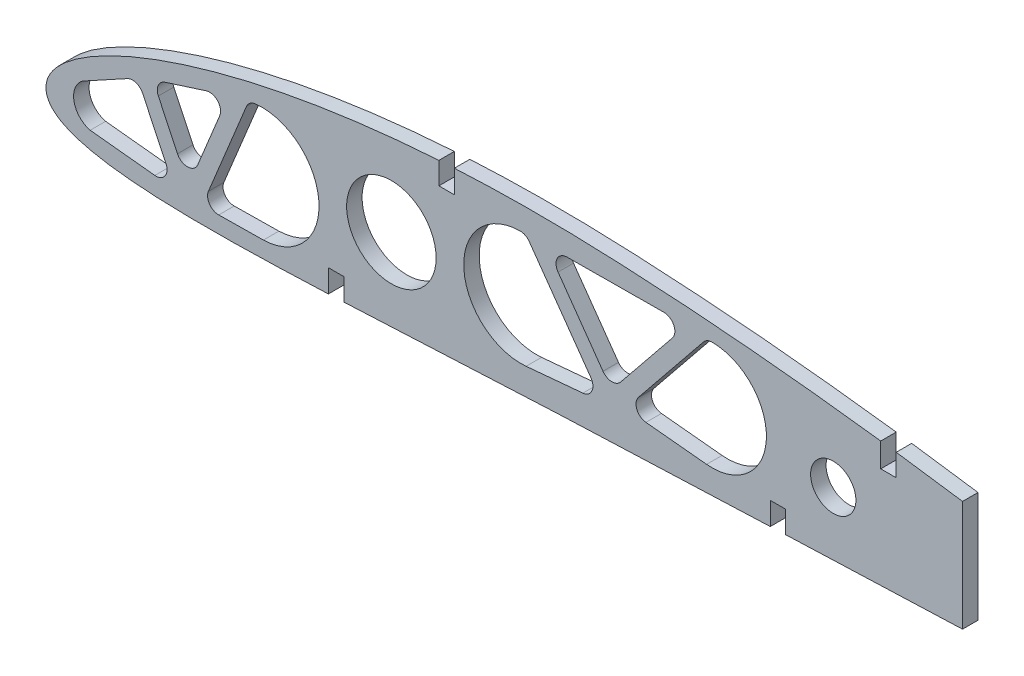
SolidWorks part; units mm, degrees
material "фанера"
ref_plane "Front" through (0, 0, 0) normal (0, 0, 1) x (1, 0, 0)
ref_plane "Top" through (0, 0, 0) normal (0, 1, 0) x (1, 0, 0)
ref_plane "Right" through (0, 0, 0) normal (1, 0, 0) x (0, 0, -1)
curve "Кривая1"
  spline degree 3 poles (0.048, 0.6214, 0) (0.0227, 0.3735, 0) (-0.0278, -0.1225, 0) (0.078, -0.8844, 0) (0.3497, -1.6388, 0) (0.8143, -2.3651, 0) (1.4635, -3.0393, 0) (2.291, -3.661, 0) (3.3059, -4.2358, 0) (4.5353, -4.7737, 0) (6.0297, -5.2822, 0) (7.869, -5.7653, 0) (10.1688, -6.2217, 0) (13.0754, -6.6396, 0) (16.7281, -6.993, 0) (21.19, -7.2473, 0) (26.4, -7.3766, 0) (32.1974, -7.3763, 0) (38.3978, -7.2614, 0) (44.8576, -7.0566, 0) (51.4865, -6.7865, 0) (58.231, -6.4723, 0) (65.0521, -6.1329, 0) (71.9108, -5.784, 0) (78.7714, -5.4397, 0) (85.6105, -5.111, 0) (92.4321, -4.805, 0) (99.255, -4.532, 0) (106.0974, -4.2783, 0) (112.9692, -4.0031, 0) (119.8644, -3.7232, 0) (126.7739, -3.4401, 0) (133.6816, -3.1587, 0) (140.5819, -2.8824, 0) (147.472, -2.6139, 0) (154.3526, -2.3556, 0) (161.225, -2.1094, 0) (168.0909, -1.8766, 0) (174.9516, -1.6586, 0) (181.8086, -1.4564, 0) (188.6632, -1.2704, 0) (195.5166, -1.1011, 0) (202.3695, -0.9486, 0) (209.2212, -0.8129, 0) (216.0668, -0.6936, 0) (222.8864, -0.5903, 0) (229.6176, -0.5029, 0) (236.0874, -0.4315, 0) (241.9808, -0.3765, 0) (246.559, -0.3395, 0) (249.1205, -0.3213, 0) (250, -0.315, 0) knots 0 0 0 0 0.002941 0.005884 0.009016 0.012365 0.016008 0.020037 0.024574 0.029784 0.035897 0.04324 0.052276 0.063635 0.077983 0.095698 0.11652 0.139661 0.164312 0.189919 0.216157 0.242838 0.269834 0.296993 0.324123 0.351139 0.378036 0.404946 0.431961 0.459078 0.486347 0.513641 0.540929 0.568176 0.59538 0.622543 0.649673 0.676775 0.703855 0.730919 0.757971 0.785018 0.812062 0.839103 0.866132 0.893099 0.919831 0.94581 0.969681 0.98959 1 1 1 1
curve "Кривая2"
  spline degree 3 poles (250, 0.315, 0) (249.1557, 0.545, 0) (246.7202, 1.2085, 0) (242.3913, 2.3583, 0) (236.8498, 3.7876, 0) (230.7799, 5.298, 0) (224.4559, 6.8129, 0) (218.0305, 8.2916, 0) (211.5624, 9.7197, 0) (205.0724, 11.0924, 0) (198.568, 12.4079, 0) (192.0524, 13.6653, 0) (185.5276, 14.8641, 0) (178.9953, 16.0034, 0) (172.4571, 17.0824, 0) (165.9143, 18.0998, 0) (159.3687, 19.0545, 0) (152.8218, 19.9449, 0) (146.2754, 20.7693, 0) (139.7314, 21.5257, 0) (133.1918, 22.212, 0) (126.6587, 22.8257, 0) (120.1368, 23.364, 0) (113.6286, 23.8247, 0) (107.1527, 24.2002, 0) (100.7411, 24.4984, 0) (94.4118, 24.6866, 0) (88.1559, 24.7401, 0) (81.949, 24.6588, 0) (75.7805, 24.441, 0) (69.6537, 24.0819, 0) (63.5754, 23.578, 0) (57.5552, 22.9249, 0) (51.6058, 22.1191, 0) (45.7444, 21.1566, 0) (39.9959, 20.0354, 0) (34.3979, 18.7563, 0) (29.0104, 17.3276, 0) (23.9258, 15.7719, 0) (19.2707, 14.1343, 0) (15.1791, 12.4833, 0) (11.7405, 10.8956, 0) (8.9594, 9.4296, 0) (6.7609, 8.1086, 0) (5.0337, 6.9246, 0) (3.6717, 5.8542, 0) (2.5921, 4.8713, 0) (1.7382, 3.9526, 0) (1.0699, 3.0809, 0) (0.5716, 2.2416, 0) (0.2158, 1.4308, 0) (0.1023, 0.8832, 0) (0.048, 0.6214, 0) knots 0 0 0 0 0.010162 0.029313 0.052012 0.076619 0.101948 0.127526 0.153184 0.178868 0.204558 0.230246 0.255926 0.281594 0.307246 0.332878 0.358485 0.384061 0.409603 0.435104 0.460559 0.485959 0.511303 0.536552 0.561723 0.586629 0.611085 0.635251 0.659272 0.683164 0.706922 0.730536 0.753983 0.777235 0.800246 0.822951 0.845237 0.866916 0.887662 0.906968 0.924203 0.938879 0.950932 0.960693 0.968647 0.975233 0.980795 0.985584 0.989782 0.993521 0.996902 1 1 1 1
sketch "Эскиз2" plane through (0, 0, 0) normal (0, 0, 1) x (1, 0, 0)
  line L0 (-1.2592, 0) -> (250.7702, 0) construction
  line L1 (250.1305, 0) -> (250.1305, 80.0888) construction
  line L2 (0, 0) -> (0, 69.7453) construction
  line L3 (62.5326, 123.1249) -> (62.5326, -48.5934) construction
  line L4 (142.5326, 131.1199) -> (142.5326, -55.0117) construction
  line L5 (62.5326, 8.5962) -> (142.5326, 8.5962) construction
  line L6 (62.5326, 8.5962) -> (150.6431, 8.5962) construction
  line L7 (175.0913, 92.567) -> (175.0913, -39.4544) construction
  line L8 (165.9405, 18.0854) -> (165.9405, -1.9504)
  line L9 (87.4969, 19.5968) -> (98.657, 3.8464)
  line L12 (107.2666, 5.069) -> (119.0427, 19.6405)
  line L13 (92.7103, 17.4282) -> (100.8475, 5.9439)
  line L14 (104.0349, 5.843) -> (113.4136, 17.4479)
  line L15 (108.6238, 1.8217) -> (119.6039, 0.7278)
  line L16 (94.3284, 20.5844) -> (111.8443, 20.705)
  line L17 (86.9285, -0.2347) -> (97.2059, 0.6983)
  line L18 (17.4887, 7.868) -> (21.7254, -1.0733)
  line L19 (29.4016, -1.5679) -> (36.2887, 15.1777)
  line L20 (20.3422, 8.8519) -> (23.813, 1.5271)
  line L21 (27.4701, 1.6228) -> (31.461, 11.3265)
  line L22 (7.9994, -2.6904) -> (19.7094, -3.9188)
  line L23 (31.2779, -4.3285) -> (39.3668, -4.221)
  line L24 (6.5801, 4.311) -> (14.7212, 8.7661)
  line L25 (21.5421, 11.6138) -> (29.0038, 13.9928)
  line L26 (72.5326, 27.406) -> (72.5326, 20.4403) construction
  line L27 (52.5326, -12.1202) -> (52.5326, -2.6904) construction
  line L28 (152.5326, 24.4982) -> (152.5326, 15.921) construction
  line L29 (132.5326, -7.5811) -> (132.5326, 3.1811) construction
  line L30 (151.1326, 20.1529) -> (151.1326, 15.7875)
  line L31 (151.1326, 15.7875) -> (153.9326, 15.7875)
  line L32 (153.9326, 15.7875) -> (153.9326, 19.7875)
  line L33 (131.1326, -3.2627) -> (131.1326, 0.8506)
  line L34 (131.1326, 0.8506) -> (133.9326, 0.8506)
  line L35 (133.9326, 0.8506) -> (133.9326, -3.1494)
  line L36 (71.1326, 24.1575) -> (71.1326, 20.1575)
  line L37 (71.1326, 20.1575) -> (73.9326, 20.1575)
  line L38 (73.9326, 20.1575) -> (73.9326, 24.3239)
  line L39 (51.1326, -6.7954) -> (51.1326, -2.6707)
  line L40 (51.1326, -2.6707) -> (53.9326, -2.6707)
  line L41 (53.9326, -2.6707) -> (53.9326, -6.6707)
  arc A0 (250, 0.315) -> (250, -0.315) centre (249.685, 0) cw
  circle A3 centre (62.5326, 8.5962) radius 8.1
  circle A5 centre (62.5326, 8.5962) radius 80 construction
  circle A6 centre (142.5326, 8.5962) radius 4.1
  arc A7 (175.0913, 16.6448) -> (175.0913, -1.657) centre (175.0913, 7.4939) ccw
  arc A10 (107.2666, 5.069) -> (108.6238, 1.8217) centre (108.8221, 3.8118) ccw
  arc A11 (85.8347, 20.4403) -> (86.9285, -0.2347) centre (85.9919, 10.0822) ccw
  arc A12 (120.6027, 20.3833) -> (119.6039, 0.7278) centre (120.5806, 10.5313) cw
  arc A13 (120.6027, 20.3833) -> (119.0427, 19.6405) centre (120.5982, 18.3834) ccw
  arc A14 (85.8347, 20.4403) -> (87.4969, 19.5968) centre (85.8651, 18.4406) cw
  arc A15 (100.8475, 5.9439) -> (104.0349, 5.843) centre (102.4794, 7.1001) ccw
  arc A16 (37.9117, 16.4041) -> (36.2887, 15.1777) centre (38.1384, 14.417) ccw
  arc A17 (98.657, 3.8464) -> (97.2059, 0.6983) centre (97.0251, 2.6901) cw
  arc A18 (92.7103, 17.4282) -> (94.3284, 20.5844) centre (94.3421, 18.5845) cw
  arc A19 (113.4136, 17.4479) -> (111.8443, 20.705) centre (111.8581, 18.7051) ccw
  arc A20 (6.5801, 4.311) -> (7.9994, -2.6904) centre (8.9558, 1.1481) ccw
  arc A21 (37.9117, 16.4041) -> (39.3668, -4.221) centre (39.0848, 6.123) cw
  arc A22 (23.813, 1.5271) -> (27.4701, 1.6228) centre (25.6204, 2.3835) ccw
  arc A23 (31.461, 11.3265) -> (29.0038, 13.9928) centre (29.6113, 12.0873) ccw
  arc A24 (20.3422, 8.8519) -> (21.5421, 11.6138) centre (22.1496, 9.7083) cw
  arc A25 (17.4887, 7.868) -> (14.7212, 8.7661) centre (15.6813, 7.0116) ccw
  arc A26 (19.7094, -3.9188) -> (21.7254, -1.0733) centre (19.9181, -1.9297) ccw
  arc A27 (29.4016, -1.5679) -> (31.2779, -4.3285) centre (31.2513, -2.3286) ccw
  circle A28 centre (175.0913, 7.4939) radius 1
  spline S0 degree 3 poles (250, 0.315) (249.1557, 0.545) (246.7202, 1.2085) (242.3913, 2.3583) (236.8498, 3.7876) (230.7799, 5.298) (224.4559, 6.8129) (218.0305, 8.2916) (211.5624, 9.7197) (205.0724, 11.0924) (198.568, 12.4079) (192.0524, 13.6653) (185.5276, 14.8641) (178.9953, 16.0034) (172.4571, 17.0824) (165.9143, 18.0998) (159.3687, 19.0545) (152.8218, 19.9449) (146.2754, 20.7693) (139.7314, 21.5257) (133.1918, 22.212) (126.6587, 22.8257) (120.1368, 23.364) (113.6286, 23.8247) (107.1527, 24.2002) (100.7411, 24.4984) (94.4118, 24.6866) (88.1559, 24.7401) (81.949, 24.6588) (75.7805, 24.441) (69.6537, 24.0819) (63.5754, 23.578) (57.5552, 22.9249) (51.6058, 22.1191) (45.7444, 21.1566) (39.9959, 20.0354) (34.3979, 18.7563) (29.0104, 17.3276) (23.9258, 15.7719) (19.2707, 14.1343) (15.1791, 12.4833) (11.7405, 10.8956) (8.9594, 9.4296) (6.7609, 8.1086) (5.0337, 6.9246) (3.6717, 5.8542) (2.5921, 4.8713) (1.7382, 3.9526) (1.0699, 3.0809) (0.5716, 2.2416) (0.2158, 1.4308) (0.1023, 0.8832) (0.048, 0.6214) knots 0 0 0 0 0.010162 0.029313 0.052012 0.076619 0.101948 0.127526 0.153184 0.178868 0.204558 0.230246 0.255926 0.281594 0.307246 0.332878 0.358485 0.384061 0.409603 0.435104 0.460559 0.485959 0.511303 0.536552 0.561723 0.586629 0.611085 0.635251 0.659272 0.683164 0.706922 0.730536 0.753983 0.777235 0.800246 0.822951 0.845237 0.866916 0.887662 0.906968 0.924203 0.938879 0.950932 0.960693 0.968647 0.975233 0.980795 0.985584 0.989782 0.993521 0.996902 1 1 1 1 construction
  spline S1 degree 3 poles (0.048, 0.6214) (0.0227, 0.3735) (-0.0278, -0.1225) (0.078, -0.8844) (0.3497, -1.6388) (0.8143, -2.3651) (1.4635, -3.0393) (2.291, -3.661) (3.3059, -4.2358) (4.5353, -4.7737) (6.0297, -5.2822) (7.869, -5.7653) (10.1688, -6.2217) (13.0754, -6.6396) (16.7281, -6.993) (21.19, -7.2473) (26.4, -7.3766) (32.1974, -7.3763) (38.3978, -7.2614) (44.8576, -7.0566) (51.4865, -6.7865) (58.231, -6.4723) (65.0521, -6.1329) (71.9108, -5.784) (78.7714, -5.4397) (85.6105, -5.111) (92.4321, -4.805) (99.255, -4.532) (106.0974, -4.2783) (112.9692, -4.0031) (119.8644, -3.7232) (126.7739, -3.4401) (133.6816, -3.1587) (140.5819, -2.8824) (147.472, -2.6139) (154.3526, -2.3556) (161.225, -2.1094) (168.0909, -1.8766) (174.9516, -1.6586) (181.8086, -1.4564) (188.6632, -1.2704) (195.5166, -1.1011) (202.3695, -0.9486) (211.4992, -0.7677) (220.6031, -0.6199) (229.6176, -0.5029) (236.0874, -0.4315) (241.9808, -0.3765) (246.559, -0.3395) (249.1205, -0.3213) (250, -0.315) knots 0 0 0 0 0.002941 0.005884 0.009016 0.012365 0.016008 0.020037 0.024574 0.029784 0.035897 0.04324 0.052276 0.063635 0.077983 0.095698 0.11652 0.139661 0.164312 0.189919 0.216157 0.242838 0.269834 0.296993 0.324123 0.351139 0.378036 0.404946 0.431961 0.459078 0.486347 0.513641 0.540929 0.568176 0.59538 0.622543 0.649673 0.676775 0.703855 0.730919 0.757971 0.785018 0.812062 0.839103 0.893099 0.919831 0.94581 0.969681 0.98959 1 1 1 1 construction
  spline S2 degree 3 poles (250, 0.315) (249.1557, 0.545) (246.7202, 1.2085) (242.3913, 2.3583) (236.8498, 3.7876) (230.7799, 5.298) (224.4559, 6.8129) (218.0305, 8.2916) (211.5624, 9.7197) (205.0724, 11.0924) (198.568, 12.4079) (192.0524, 13.6653) (185.5276, 14.8641) (178.9953, 16.0034) (172.4571, 17.0824) (165.9143, 18.0998) (159.7397, 19.0004) (155.7443, 19.5471) (153.9326, 19.7875) knots 0 0 0 0 0.010162 0.029313 0.052012 0.076619 0.101948 0.127526 0.153184 0.178868 0.204558 0.230246 0.255926 0.281594 0.307246 0.332878 0.358485 0.379707 0.379707 0.379707 0.379707
  spline S3 degree 3 poles (0.048, 0.6214) (0.0227, 0.3735) (-0.0278, -0.1225) (0.078, -0.8844) (0.3497, -1.6388) (0.8143, -2.3651) (1.4635, -3.0393) (2.291, -3.661) (3.3059, -4.2358) (4.5353, -4.7737) (6.0297, -5.2822) (7.869, -5.7653) (10.1688, -6.2217) (13.0754, -6.6396) (16.7281, -6.993) (21.19, -7.2473) (26.4, -7.3766) (32.1974, -7.3763) (38.3978, -7.2614) (44.7521, -7.06) (49.0233, -6.8868) (51.1326, -6.7954) knots 0 0 0 0 0.002941 0.005884 0.009016 0.012365 0.016008 0.020037 0.024574 0.029784 0.035897 0.04324 0.052276 0.063635 0.077983 0.095698 0.11652 0.139661 0.164312 0.189919 0.214908 0.214908 0.214908 0.214908
  spline S4 degree 3 poles (151.1326, 20.1529) (149.5127, 20.3609) (145.7129, 20.8343) (139.7314, 21.5257) (133.1918, 22.212) (126.6587, 22.8257) (120.1368, 23.364) (113.6286, 23.8247) (107.1527, 24.2002) (100.7411, 24.4984) (94.4118, 24.6866) (88.1559, 24.7401) (81.949, 24.6588) (77.2124, 24.4916) (74.545, 24.3569) (73.9326, 24.3239) knots 0.390637 0.390637 0.390637 0.390637 0.409603 0.435104 0.460559 0.485959 0.511303 0.536552 0.561723 0.586629 0.611085 0.635251 0.659272 0.683164 0.690286 0.690286 0.690286 0.690286
  spline S5 degree 3 poles (133.9326, -3.1494) (136.1503, -3.0598) (140.6644, -2.8792) (147.472, -2.6139) (154.3526, -2.3556) (161.225, -2.1094) (168.0909, -1.8766) (174.9516, -1.6586) (181.8086, -1.4564) (188.6632, -1.2704) (195.5166, -1.1011) (202.3695, -0.9486) (211.4992, -0.7677) (220.6031, -0.6199) (229.6176, -0.5029) (236.0874, -0.4315) (241.9808, -0.3765) (246.559, -0.3395) (249.1205, -0.3213) (250, -0.315) knots 0.541906 0.541906 0.541906 0.541906 0.568176 0.59538 0.622543 0.649673 0.676775 0.703855 0.730919 0.757971 0.785018 0.812062 0.839103 0.893099 0.919831 0.94581 0.969681 0.98959 1 1 1 1
  spline S6 degree 3 poles (71.1326, 24.1575) (70.636, 24.1252) (68.1106, 23.954) (63.5754, 23.578) (57.5552, 22.9249) (51.6058, 22.1191) (45.7444, 21.1566) (39.9959, 20.0354) (34.3979, 18.7563) (29.0104, 17.3276) (23.9258, 15.7719) (19.2707, 14.1343) (15.1791, 12.4833) (11.7405, 10.8956) (8.9594, 9.4296) (6.7609, 8.1086) (5.0337, 6.9246) (3.6717, 5.8542) (2.5921, 4.8713) (1.7382, 3.9526) (1.0699, 3.0809) (0.5716, 2.2416) (0.2158, 1.4308) (0.1023, 0.8832) (0.048, 0.6214) knots 0.701143 0.701143 0.701143 0.701143 0.706922 0.730536 0.753983 0.777235 0.800246 0.822951 0.845237 0.866916 0.887662 0.906968 0.924203 0.938879 0.950932 0.960693 0.968647 0.975233 0.980795 0.985584 0.989782 0.993521 0.996902 1 1 1 1
  spline S7 degree 3 poles (53.9326, -6.6707) (55.3566, -6.6057) (59.0587, -6.4311) (65.0521, -6.1329) (71.9108, -5.784) (78.7714, -5.4397) (85.6105, -5.111) (92.4321, -4.805) (99.255, -4.532) (106.0974, -4.2783) (112.9692, -4.0031) (119.8644, -3.7232) (125.9231, -3.4749) (129.6799, -3.3217) (131.1326, -3.2627) knots 0.225966 0.225966 0.225966 0.225966 0.242838 0.269834 0.296993 0.324123 0.351139 0.378036 0.404946 0.431961 0.459078 0.486347 0.513641 0.53085 0.53085 0.53085 0.53085
  point P15 (62.5326, 0)
  point P16 (142.5326, 0)
  point P21 (62.5326, 23.4501)
  point P22 (62.5326, -6.2577)
  point P26 (175.0913, 16.6448)
  point P28 (175.0913, -1.657)
  point P52 (119.6039, 20.3348)
  point P55 (86.9285, 20.3991)
  point P58 (102.3746, 3.7886)
  point P65 (100.665, 1.0123)
  point P86 (25.7497, -2.5601)
  point P88 (23.2497, -4.2901)
  point P91 (28.2497, -4.3687)
  dimension "D1" = 0.4455
  dimension "D6" = 16.2
  dimension "D7" = 160
  dimension "D9" = 8.2
  dimension "D12" = 9.1509
  dimension "D21" = 2
  dimension "D22" = 2
  dimension "D23" = 2
  dimension "D19" = 2
  dimension "D29" = 2
  dimension "D14" = 2
  dimension "D30" = 2
  dimension "D2" = 250.1305
  dimension "D3" = 62.5326
  dimension "D4" = 80
  dimension "D5" = 29.7079
  dimension "D8" = 14.8539
  dimension "D10" = 0
  dimension "D11" = 175.0913
  dimension "D13" = 67.8
  dimension "D15" = 5
  dimension "D16" = 8
  dimension "D17" = 3
  dimension "D18" = 3
  dimension "D20" = 5
  dimension "D24" = 5
  dimension "D25" = 3
  dimension "D26" = 3
  dimension "D27" = 5
  dimension "D28" = 2.5
  dimension "D31" = 10
  dimension "D32" = 10
  dimension "D33" = 10
  dimension "D34" = 10
  dimension "D35" = 2.8
  dimension "D36" = 1.4
  dimension "D37" = 4
  dimension "D38" = 2.8
  dimension "D39" = 1.4
  dimension "D40" = 4
  dimension "D41" = 2.8
  dimension "D42" = 1.4
  dimension "D43" = 4
  dimension "D44" = 1.4
  dimension "D45" = 2.8
  dimension "D46" = 4
extrude "Бобышка-Вытянуть2" add sketch "Эскиз2" along normal mid plane 2.8 contours S2 S3 L8 L20 A24 L25 A23 L21 A22 L9 A17 L17 A11 A14 A3 A6 A13 A12 L15 A10 L12 A19 L14 A15 L13 A18 L16 A26 L22 A20 L24 A25 L18 A27 L19 A16 A21 L23
equation "\"D3@Эскиз2\"=\"D2@Эскиз2\"/4"
equation "\"D8@Эскиз2\"=\"D5@Эскиз2\"/2"
equation "\"D7@Эскиз2\"=\"D4@Эскиз2\"*2"
equation "\"D11@Эскиз2\"=\"D2@Эскиз2\"*0.7"
equation "\"D28@Эскиз2\"=\"D27@Эскиз2\"/2"
